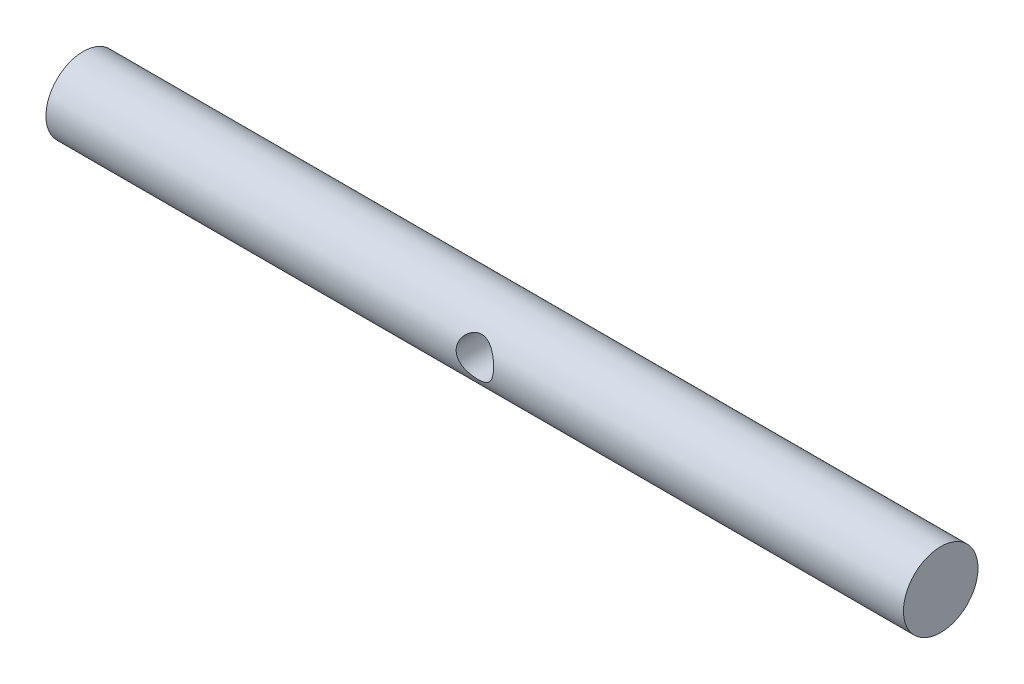
SolidWorks part; units mm, degrees
ref_plane "Front" through (0, 0, 0) normal (0, 0, 1) x (1, 0, 0)
ref_plane "Top" through (0, 0, 0) normal (0, 1, 0) x (1, 0, 0)
ref_plane "Right" through (0, 0, 0) normal (1, 0, 0) x (0, 0, -1)
sketch "草图1" plane through (0, 0, 0) normal (1, 0, 0) x (0, 0, -1)
  circle A0 centre (0, 0) radius 12.7
  dimension "D1" = 25.4
extrude "凸台-拉伸1" add sketch "草图1" along normal blind 292.1
sketch "草图2" plane through (0, 0, 0) normal (0, 0, 1) x (1, 0, 0)
  line L8 (0, 12.7) -> (0, -12.7) construction
  circle A0 centre (146.05, 1.0854) radius 6.35
  point P2 (184.9663, -1.3901)
  point P7 (153.1467, 0)
  point P8 (0, 0)
  point P9 (150.6928, 1.0854)
  dimension "D1" = 12.7
  dimension "D2" = 146.05
extrude "切除-拉伸1" cut sketch "草图2" along normal through all both and the other way through all
